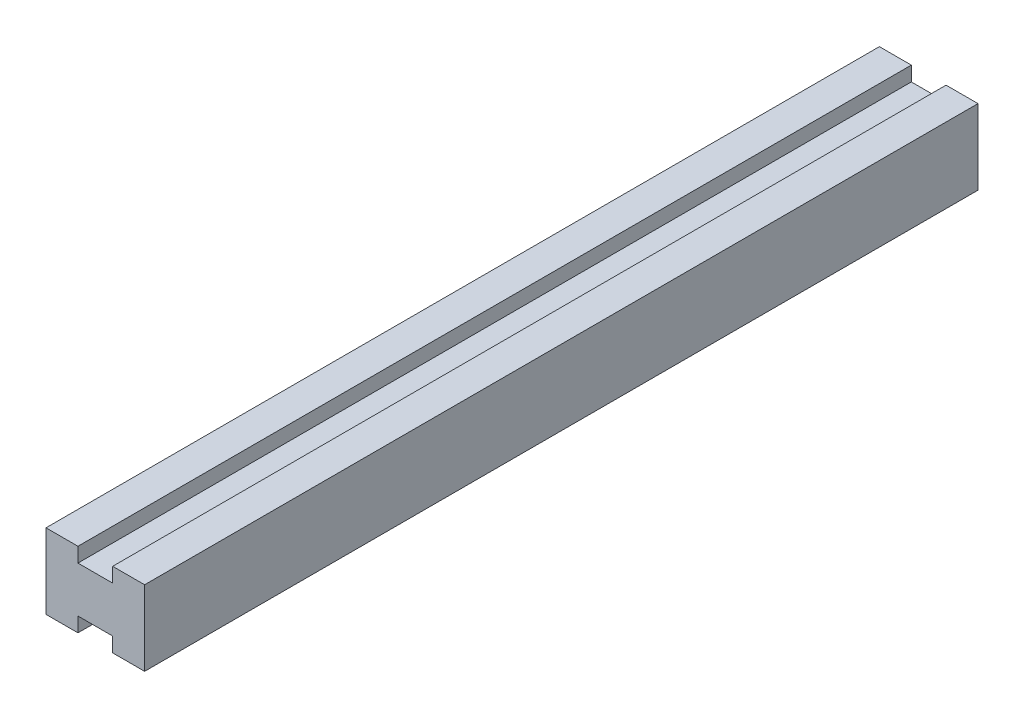
SolidWorks part; units mm, degrees
ref_plane "Front Plane" through (0, 0, 0) normal (0, 0, 1) x (1, 0, 0)
ref_plane "Top Plane" through (0, 0, 0) normal (0, 1, 0) x (1, 0, 0)
ref_plane "Right Plane" through (0, 0, 0) normal (1, 0, 0) x (0, 0, -1)
sketch "Sketch1" plane through (0, 0, 0) normal (0, 0, 1) x (1, 0, 0)
  line L8 (-1.3, 2.75) -> (-3.6, 2.75)
  line L9 (-1.3, 2.75) -> (-1.3, 1.7)
  line L10 (-1.3, -2.65) -> (-3.6, -2.65)
  line L11 (-3.6, 2.75) -> (-3.6, -2.65)
  line L14 (-1.3, -1.6) -> (-1.3, -2.65)
  line L15 (1.2, 2.75) -> (3.5, 2.75)
  line L16 (1.2, 2.75) -> (1.2, 1.7)
  line L17 (1.2, -2.65) -> (3.5, -2.65)
  line L18 (3.5, 2.75) -> (3.5, -2.65)
  line L21 (1.2, -1.6) -> (1.2, -2.65)
  line L22 (1.2, -1.6) -> (-1.3, -1.6)
  line L23 (1.2, 1.7) -> (-1.3, 1.7)
  point P0 (0, 0)
  dimension "D1" = 7.1
  dimension "D2" = 2.5
  dimension "D4" = 5.4
extrude "Boss-Extrude1" add sketch "Sketch1" along normal blind 60 contours L8 L11 L10 L14 L22 L21 L17 L18 L15 L16 L23 L9
